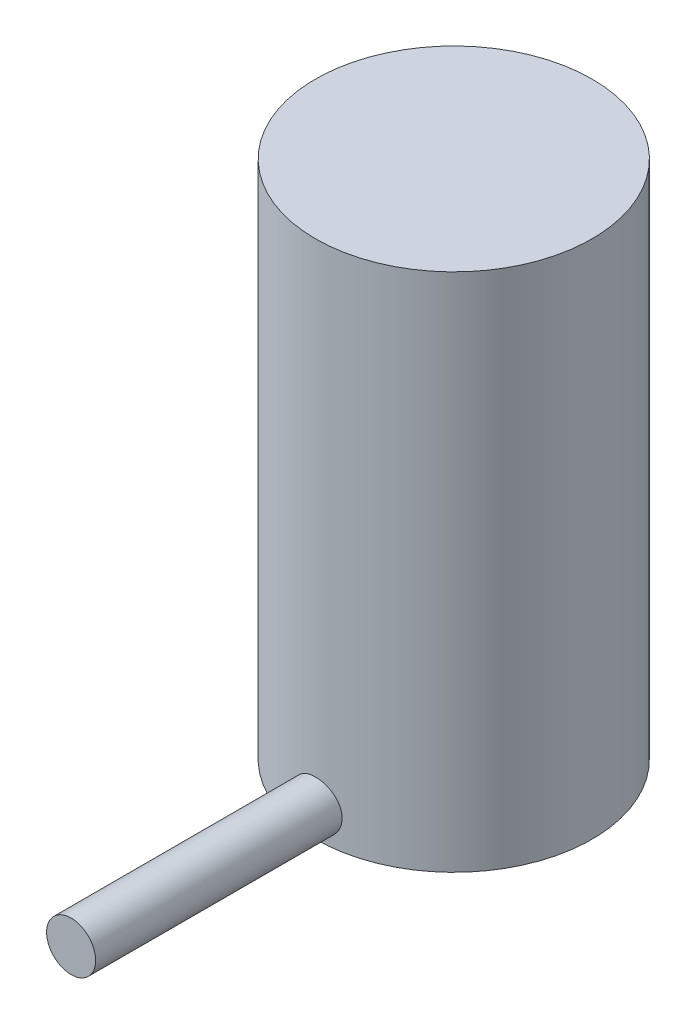
SolidWorks part; units mm, degrees
ref_plane "Front Plane" through (0, 0, 0) normal (0, 0, 1) x (1, 0, 0)
ref_plane "Top Plane" through (0, 0, 0) normal (0, 1, 0) x (1, 0, 0)
ref_plane "Right Plane" through (0, 0, 0) normal (1, 0, 0) x (0, 0, -1)
sketch "Sketch2" plane through (0, 0, 0) normal (0, 1, 0) x (1, 0, 0)
  circle A0 centre (0, 0) radius 17.907
  dimension "D1" = 35.814
extrude "Boss-Extrude1" add sketch "Sketch2" along normal blind 69.85 contours A0
sketch "Sketch3" plane through (0, 0, 0) normal (0, 0, 1) x (1, 0, 0)
  line L0 (0, 0) -> (0, 6.35)
  circle A0 centre (0, 6.35) radius 3.175
extrude "Boss-Extrude2" add sketch "Sketch3" along normal blind 49.53 contours A0
sketch "Sketch4" plane through (0, 0, 0) normal (0, -1, 0) x (1, 0, 0)
  circle A0 centre (0, 0) radius 17.907
extrude "Cut-Extrude1" cut sketch "Sketch4" against normal blind 2.54
